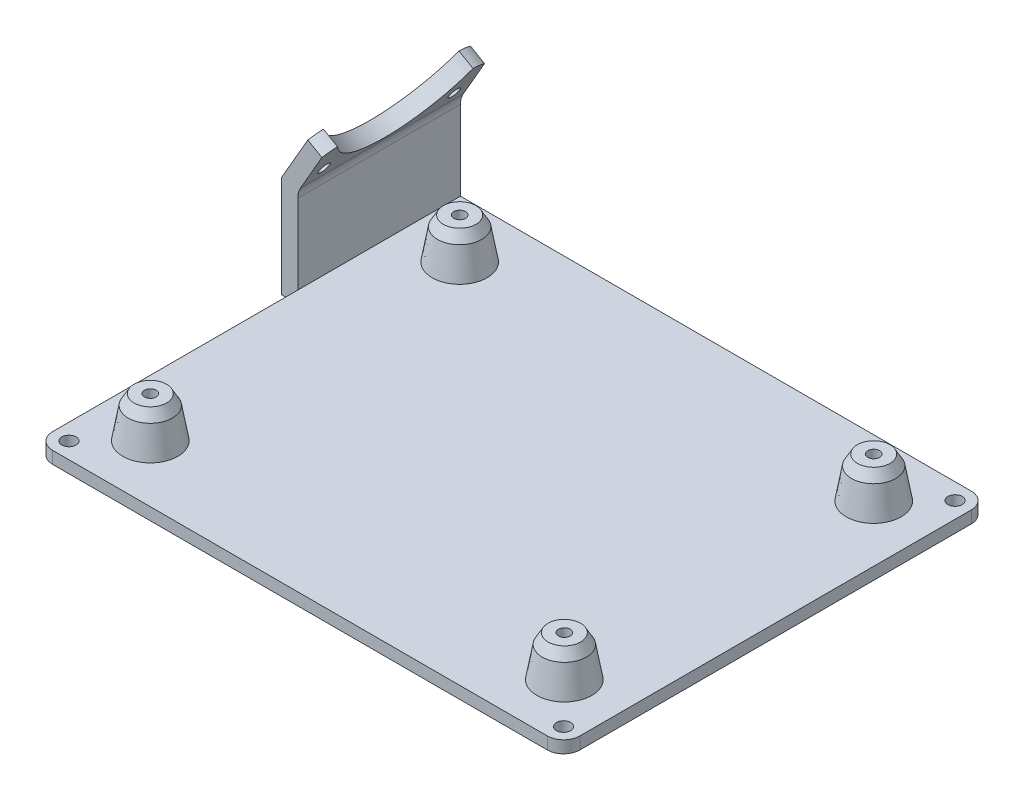
SolidWorks part; units mm, degrees
ref_plane "Front Plane" through (0, 0, 0) normal (0, 0, 1) x (1, 0, 0)
ref_plane "Top Plane" through (0, 0, 0) normal (0, 1, 0) x (1, 0, 0)
ref_plane "Right Plane" through (0, 0, 0) normal (1, 0, 0) x (0, 0, -1)
sketch "Sketch1" plane through (0, 0, 0) normal (0, 1, 0) x (1, 0, 0)
  line L0 (0, 0) -> (0, 42.15) construction
  line L1 (-54.835, -42.15) -> (54.835, -42.15)
  line L2 (-54.835, -42.15) -> (-54.835, 42.15)
  line L3 (-54.835, 42.15) -> (54.835, 42.15)
  line L4 (54.835, -42.15) -> (54.835, 42.15)
  line L5 (-54.835, -42.15) -> (54.835, 42.15) construction
  line L6 (-54.835, 42.15) -> (54.835, -42.15) construction
  line L7 (0, 0) -> (54.835, 0) construction
  circle A0 centre (-50.925, 38.05) radius 1.75
  circle A1 centre (50.925, 38.05) radius 1.75
  circle A2 centre (50.925, -38.05) radius 1.75
  circle A3 centre (-50.925, -38.05) radius 1.75
  point P0 (0, 0)
  dimension "D3" = 3.5
  dimension "D4" = 101.85
  dimension "D5" = 76.1
  dimension "D1" = 109.67
  dimension "D2" = 84.3
sketch "Sketch2" plane through (0, 0, 0) normal (0, 1, 0) x (1, 0, 0)
  line L8 (-64.835, 52.15) -> (-64.835, -52.15)
  line L9 (-64.835, -52.15) -> (64.835, -52.15)
  line L10 (64.835, -52.15) -> (64.835, 52.15)
  line L11 (64.835, 52.15) -> (-64.835, 52.15)
  line L12 (-64.835, 47.15) -> (-64.835, -48.15)
  line L13 (-60.835, -52.15) -> (60.835, -52.15)
  line L14 (64.835, -48.15) -> (64.835, 48.15)
  line L15 (60.835, 52.15) -> (-59.835, 52.15)
  circle A0 centre (-59.835, 47.15) radius 1.75
  arc A1 (-64.835, 47.15) -> (-59.835, 52.15) centre (-59.835, 47.15) cw
  arc A2 (-64.835, -48.15) -> (-60.835, -52.15) centre (-60.835, -48.15) ccw
  arc A3 (60.835, -52.15) -> (64.835, -48.15) centre (60.835, -48.15) ccw
  arc A4 (64.835, 48.15) -> (60.835, 52.15) centre (60.835, 48.15) ccw
  circle A5 centre (60.835, 48.15) radius 1.75
  circle A6 centre (60.835, -48.15) radius 1.75
  circle A7 centre (-60.835, -48.15) radius 1.75
  dimension "D2" = 3.5
  dimension "D3" = 5
  dimension "D4" = 4
  dimension "D1" = 10
extrude "Boss-Extrude1" add sketch "Sketch2" along normal blind 3
sketch "Sketch3" plane through (0, 3, 0) normal (0, 1, 0) x (1, 0, 0)
  circle A0 centre (-50.925, 38.05) radius 5
  circle A1 centre (50.925, 38.05) radius 5
  circle A2 centre (-50.925, -38.05) radius 5
  circle A3 centre (50.925, -38.05) radius 5
  dimension "D1" = 10
extrude "Boss-Extrude2" add sketch "Sketch3" against normal up to surface (3 mm away) draft 10 from offset 10 draft outward yes
sketch "Sketch4" plane through (0, 13, 0) normal (0, 1, 0) x (1, 0, 0)
  circle A0 centre (-50.925, 38.05) radius 1.45
  circle A1 centre (50.925, 38.05) radius 1.45
  circle A2 centre (50.925, -38.05) radius 1.45
  circle A3 centre (-50.925, -38.05) radius 1.45
  dimension "D1" = 2.9
extrude "Cut-Extrude1" cut sketch "Sketch4" against normal through all
chamfer "Chamfer1" distance 1 angle 60 4 edges at (-50.925, 13, 43.05) (50.925, 13, 43.05) (50.925, 13, -33.05) (-50.925, 13, -33.05)
sketch "Sketch5" plane through (-64.835, 0, 0) normal (-1, 0, 0) x (0, 0, 1)
  line L0 (-52.15, 0) -> (-52.15, 25)
  line L1 (-47.15, 0) -> (48.15, 0) construction
  line L2 (-52.15, 25) -> (-12.15, 25)
  line L3 (-12.15, 25) -> (-12.15, 0)
  line L4 (42.15, 0) -> (-42.15, 0) construction
  line L5 (-12.15, 0) -> (-52.15, 0)
  line L6 (-52.15, 27) -> (-12.15, 27) construction
  line L7 (-34.05, 13) -> (-42.05, 13) construction
  line L9 (-52.15, 3) -> (-52.15, 0) construction
  dimension "D1" = 40
  dimension "D2" = 14
  dimension "D3" = 2
extrude "Boss-Extrude3" add sketch "Sketch5" along normal blind 4
sketch "Sketch6" plane through (0, 0, 0) normal (0, -1, 0) x (1, 0, 0)
  line L0 (-59.835, -52.15) -> (-64.835, -52.15)
  line L1 (-64.835, -52.15) -> (-64.835, -47.15)
  arc A0 (-64.835, -47.15) -> (-59.835, -52.15) centre (-59.835, -47.15) ccw construction
  arc A1 (-64.835, -47.15) -> (-59.835, -52.15) centre (-59.835, -47.15) ccw
extrude "Boss-Extrude4" add sketch "Sketch6" against normal up to surface (3 mm away) up to face at (50.925, 3, 44.8133)
sketch "Sketch7" plane through (0, 0, -52.15) normal (0, 0, -1) x (-1, 0, 0)
  line L0 (52.6047, 45.1117) -> (64.835, 23.9282)
  line L1 (52.6047, 45.1117) -> (56.0688, 47.1117)
  line L2 (56.0688, 47.1117) -> (68.835, 25)
  line L3 (64.835, 25) -> (64.835, 3) construction
  line L4 (64.835, 23.9282) -> (64.835, 25)
  line L5 (64.835, 25) -> (68.835, 25)
  dimension "D1" = 150
  dimension "D2" = 4
extrude "Boss-Extrude5" add sketch "Sketch7" against normal up to surface (40 mm away) contours L2 L5 L4 L0 L1 up to face at (-66.435, 10.6, -12.15)
sketch "Sketch8" plane through (-62.4516, 36.0564, 0) normal (-0.866, 0.5, 0) x (0, 0, 1)
  line L0 (-12.15, -12.7669) -> (-12.15, 12.7655) construction
  line L1 (-12.15, -12.7669) -> (-52.15, -12.7669) construction
  line L2 (-52.15, 12.7655) -> (-52.15, 0.1613)
  line L3 (-52.15, 12.7655) -> (-50.3096, 12.7655)
  line L4 (-12.15, 12.7655) -> (-52.15, 12.7655) construction
  line L5 (-52.15, 12.7655) -> (-52.15, -12.7669) construction
  line L6 (-12.15, 12.7655) -> (-13.9904, 12.7655)
  line L7 (-12.15, 12.7655) -> (-12.15, 0.1613)
  circle A0 centre (-32.15, 9.2331) radius 18.5
  circle A2 centre (-48.15, -6.7669) radius 1.4
  circle A3 centre (-16.15, -6.7669) radius 1.4
  arc A4 (-48.8174, 1.2052) -> (-52.15, 0.1613) centre (-48.15, -6.7669) ccw
  arc A6 (-15.4826, 1.2052) -> (-12.15, 0.1613) centre (-16.15, -6.7669) cw
  line B0 (-48.15, -6.7669) -> (-16.15, -6.7669) construction
  line B1 (-48.15, -6.7669) -> (-48.15, 25.2331) construction
  line B2 (-48.15, 25.2331) -> (-16.15, 25.2331) construction
  line B3 (-16.15, -6.7669) -> (-16.15, 25.2331) construction
  line B4 (-32.15, 25.2331) -> (-32.15, -6.7669) construction
  line B5 (-48.15, 9.2331) -> (-16.15, 9.2331) construction
  line B6 (-12.15, -10.7669) -> (-52.15, -10.7669) construction
  line B7 (-12.15, -10.7669) -> (-12.15, 29.2331) construction
  line B8 (-12.15, 29.2331) -> (-52.15, 29.2331) construction
  line B9 (-52.15, -10.7669) -> (-52.15, 29.2331) construction
  line B10 (-32.15, 29.2331) -> (-32.15, -10.7669) construction
  line B11 (-12.15, 9.2331) -> (-52.15, 9.2331) construction
  circle B12 centre (-48.15, 25.2331) radius 1.6
  circle B13 centre (-16.15, 25.2331) radius 1.6
  circle B14 centre (-48.15, -6.7669) radius 1.6
  circle B15 centre (-16.15, -6.7669) radius 1.6
  circle B16 centre (-32.15, 9.2331) radius 18.5 construction
  line M7 (-12.15, -12.7669) -> (-12.15, 12.7655)
  line M8 (-12.15, 12.7655) -> (-52.15, 12.7655)
  line M9 (-52.15, 12.7655) -> (-52.15, -12.7669)
  dimension "D1" = 2.8
  dimension "D3" = 8
  dimension "D2" = 22
sketch_block_instance "Block-4010_Axial_Fan-3"
sketch_block "Block-4010_Axial_Fan" parameters "D1"=3.2, "D3"=27.728, "D2"=40
extrude "Cut-Extrude3" cut sketch "Sketch8" against normal up to surface (4 mm away) contours A4 A0 M8 M9 | A0 M8 | A0 A6 M7 M8 | A3 | A2 up to face at (-58.7199, 34.52, -32.15)
fillet "Fillet1" radius 5 1 edges at (-64.835, 23.9282, -32.15)
